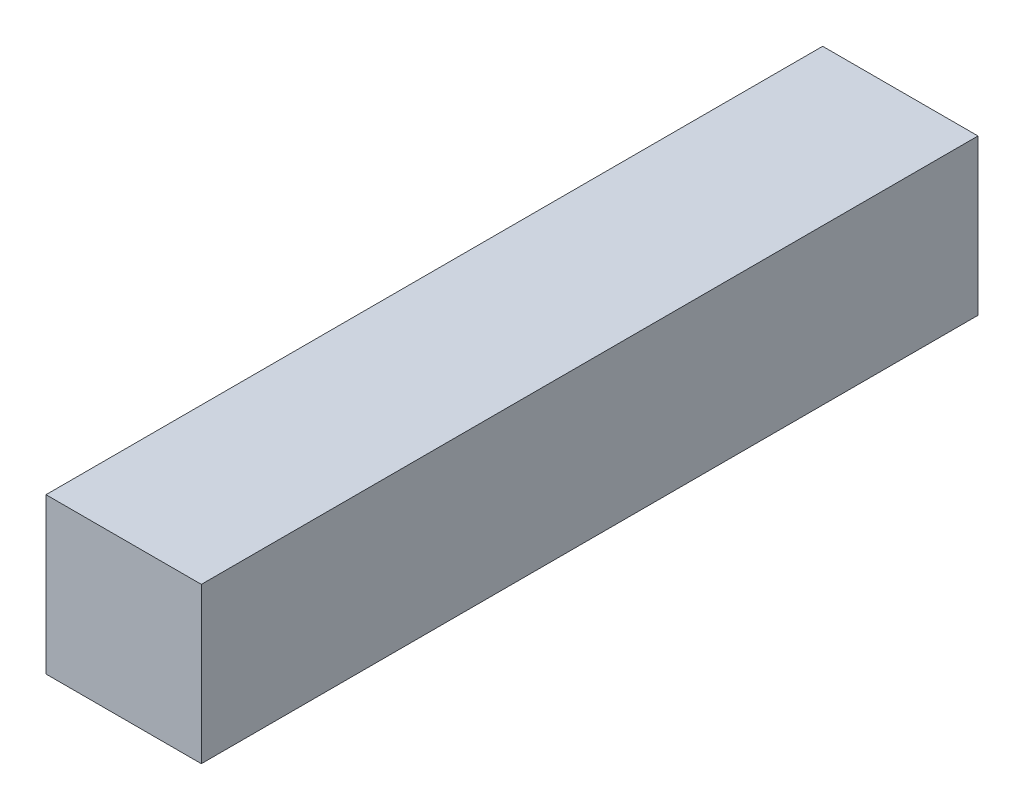
SolidWorks part; units mm, degrees
material "Commercially Pure CP-Ti UNS R50400 (SS)"
ref_plane "Front" through (0, 0, 0) normal (0, 0, 1) x (1, 0, 0)
ref_plane "Top" through (0, 0, 0) normal (0, 1, 0) x (1, 0, 0)
ref_plane "Right" through (0, 0, 0) normal (1, 0, 0) x (0, 0, -1)
sketch "Sketch1" plane through (0, 0, 0) normal (0, 0, 1) x (1, 0, 0)
  line L1 (-12.7, -12.7) -> (12.7, -12.7)
  line L2 (-12.7, -12.7) -> (-12.7, 12.7)
  line L3 (-12.7, 12.7) -> (12.7, 12.7)
  line L4 (12.7, -12.7) -> (12.7, 12.7)
  line L5 (-12.7, -12.7) -> (12.7, 12.7) construction
  line L6 (-12.7, 12.7) -> (12.7, -12.7) construction
  point P0 (0, 0)
  dimension "D1" = 25.4
extrude "Boss-Extrude1" add sketch "Sketch1" along normal blind 127
